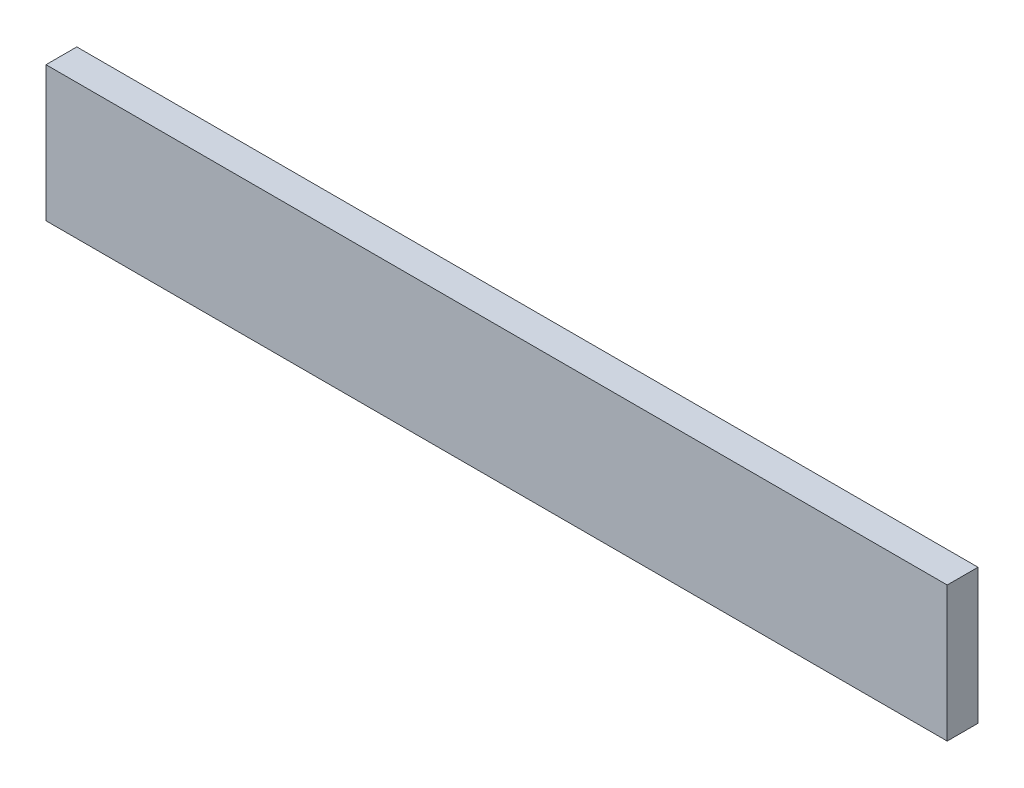
SolidWorks part; units mm, degrees
ref_plane "Front Plane" through (0, 0, 0) normal (0, 0, 1) x (1, 0, 0)
ref_plane "Top Plane" through (0, 0, 0) normal (0, 1, 0) x (1, 0, 0)
ref_plane "Right Plane" through (0, 0, 0) normal (1, 0, 0) x (0, 0, -1)
sketch "Sketch1" plane through (0, 0, 0) normal (0, 0, 1) x (1, 0, 0)
  line L1 (-300, 90) -> (300, 90)
  line L2 (-300, 90) -> (-300, 0)
  line L3 (-300, 0) -> (300, 0)
  line L4 (300, 90) -> (300, 0)
  point P4 (0, 0)
  dimension "D1" = 600
  dimension "D2" = 90
extrude "Boss-Extrude1" add sketch "Sketch1" along normal blind 20.5
